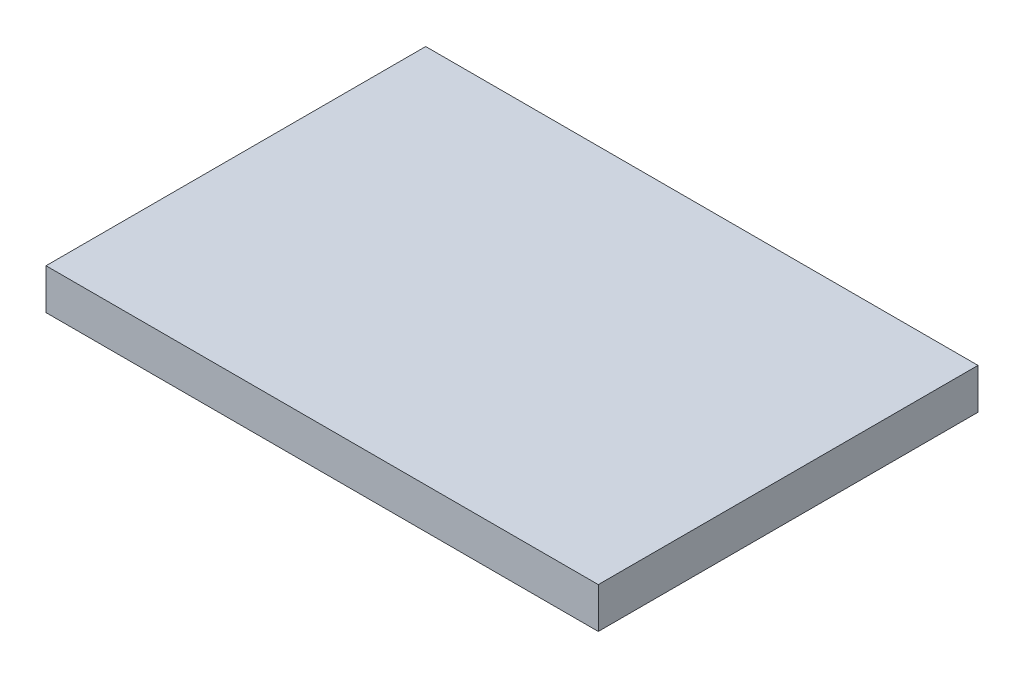
SolidWorks part; units mm, degrees
ref_plane "Front Plane" through (0, 0, 0) normal (0, 0, 1) x (1, 0, 0)
ref_plane "Top Plane" through (0, 0, 0) normal (0, 1, 0) x (1, 0, 0)
ref_plane "Right Plane" through (0, 0, 0) normal (1, 0, 0) x (0, 0, -1)
sketch "Sketch1" plane through (0, 0, 0) normal (0, 1, 0) x (1, 0, 0)
  line L1 (-136, 93.5) -> (136, 93.5)
  line L2 (-136, 93.5) -> (-136, -93.5)
  line L3 (-136, -93.5) -> (136, -93.5)
  line L4 (136, 93.5) -> (136, -93.5)
extrude "Boss-Extrude1" add sketch "Sketch1" along normal blind 20
